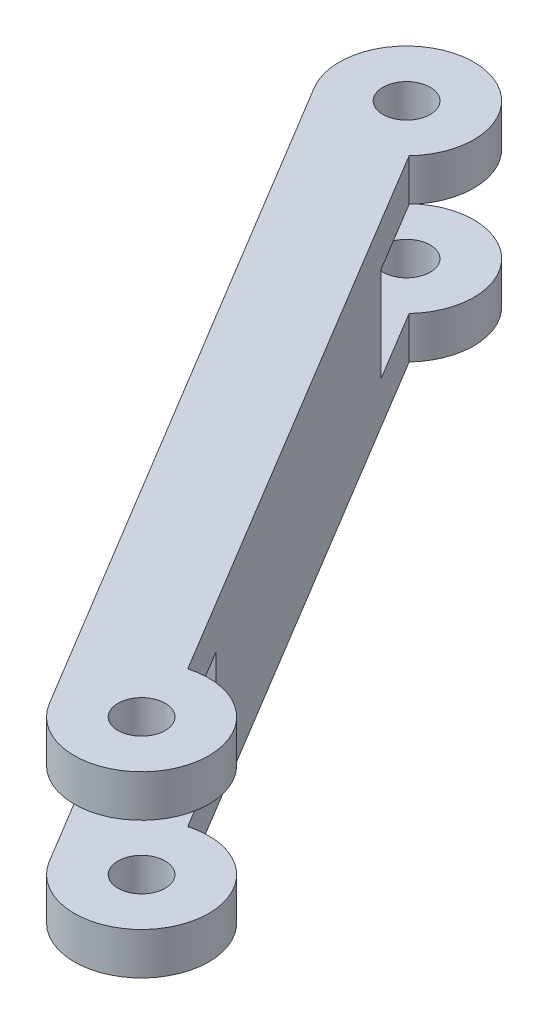
SolidWorks part; units mm, degrees
ref_plane "Front Plane" through (0, 0, 0) normal (0, 0, 1) x (1, 0, 0)
ref_plane "Top Plane" through (0, 0, 0) normal (0, 1, 0) x (1, 0, 0)
ref_plane "Right Plane" through (0, 0, 0) normal (1, 0, 0) x (0, 0, -1)
sketch "Sketch1" plane through (0, 0, 0) normal (0, 1, 0) x (1, 0, 0)
  line L0 (47.2297, 219.0186) -> (732.563, 219.0186) construction
  line L1 (-20.4095, 38.1271) -> (-1.325, 6.4308)
  line L2 (-15.3458, 37.5761) -> (0.5353, 11.1578)
  circle A0 centre (-17.6681, 39.7778) radius 1.125
  arc A1 (-15.3458, 37.5761) -> (-20.4095, 38.1271) centre (-17.6681, 39.7778) ccw
  circle A2 centre (1.4164, 8.0815) radius 1.125
  arc A3 (-1.325, 6.4308) -> (0.5353, 11.1578) centre (1.4164, 8.0815) ccw
extrude "Boss-Extrude8" add sketch "Sketch1" along normal blind 8.5
sketch "Sketch7" plane through (1.8693, 0, -1.1255) normal (-0.8567, 0, 0.5158) x (0.5158, 0, 0.8567)
  line L0 (-43.191, 8.5) -> (-6.1927, 8.5) construction
  line L1 (-36.191, 2) -> (-57.4574, 2)
  line L2 (-36.191, 2) -> (-36.191, 6.5)
  line L3 (-36.191, 6.5) -> (-57.4574, 6.5)
  line L4 (-57.4574, 2) -> (-57.4574, 6.5)
  line L5 (-43.191, 8.5) -> (-43.191, 0) construction
  line L6 (-6.1927, 8.5) -> (-6.1927, 0) construction
  line L7 (-13.1927, 6.5) -> (3.2524, 6.5)
  line L8 (-13.1927, 6.5) -> (-13.1927, 2)
  line L9 (-13.1927, 2) -> (3.2524, 2)
  line L10 (3.2524, 6.5) -> (3.2524, 2)
  dimension "D1" = 4.5
  dimension "D2" = 2
  dimension "D3" = 7
  dimension "D4" = 7
extrude "Cut-Extrude4" cut sketch "Sketch7" against normal blind 8.5
